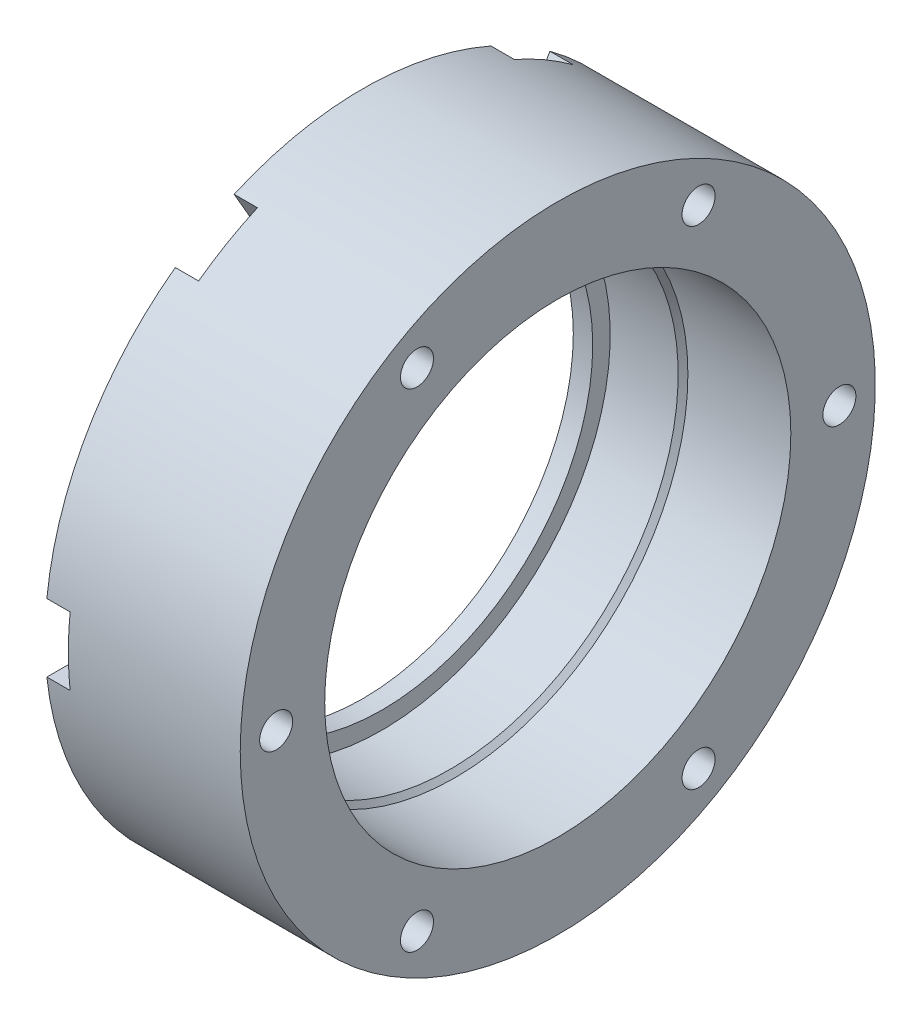
SolidWorks part; units mm, degrees
material "6063-T5"
ref_plane "Front" through (0, 0, 0) normal (0, 0, 1) x (1, 0, 0)
ref_plane "Top" through (0, 0, 0) normal (0, 1, 0) x (1, 0, 0)
ref_plane "Right" through (0, 0, 0) normal (1, 0, 0) x (0, 0, -1)
sketch "Croquis2" plane through (0, 0, 0) normal (0, 1, 0) x (1, 0, 0)
  line L0 (0, 32.7) -> (20.1, 32.7)
  line L1 (0, -55) -> (0, 55) construction
  line L2 (20.1, 32.7) -> (20.1, 24)
  line L3 (20.1, 24) -> (9.5, 24)
  line L4 (9.5, 24) -> (9, 23.5)
  line L5 (9, 23.5) -> (2, 23.5)
  line L6 (2, 23.5) -> (2, 21.7)
  line L7 (2, 21.7) -> (0, 21.7)
  line L8 (0, 21.7) -> (0, 32.7)
  line L9 (-55, 0) -> (55, 0) construction
  line L10 (-10.7507, 0) -> (41.8865, 0) construction
  dimension "D1" = 2
  dimension "D2" = 32.7
  dimension "D3" = 24
  dimension "D4" = 23.5
  dimension "D5" = 21.7
  dimension "D6" = 45
  dimension "D7" = 10.6
  dimension "D8" = 7
revolve "Revolución1" add sketch "Croquis2" angle 360 about L10
hole_wizard "Refrentado para tornillo con cabeza troncocónica de M31" positions "Croquis3" profile "Croquis5" counterbore size "M3" standard "Ansi Metric" end condition up to next
sketch "Croquis3" plane through (0, 0, 0) normal (-1, 0, 0) x (0, 0, 1)
  line L0 (0, 0) -> (14.5, 25.1147) construction
  line L3 (0, -11.055) -> (0, 11.055) construction
  point P0 (14.5, 25.1147)
  point P16 (29, 0)
  point P17 (14.5, -25.1147)
  point P18 (-14.5, -25.1147)
  point P19 (-29, 0)
  point P20 (-14.5, 25.1147)
  dimension "D1" = 29
  dimension "D2" = 30
  dimension "D3" = 6
sketch "Croquis5" plane through (0, 25.1147, 14.5) normal (0, 1, 0) x (0, 0, 1)
  line L0 (0, 0) -> (0, 20.1)
  line L1 (0, 20.1) -> (1.7, 20.1)
  line L3 (1.7, 20.1) -> (1.7, 2.4)
  line L4 (1.7, 2.4) -> (3.5, 2.4)
  line L5 (3.5, 2.4) -> (3.5, 0)
  line L7 (3.5, 0) -> (0, 0)
  line L11 (0, -6.35) -> (0, 107.95) construction
  dimension "Diámetro de taladro hasta el siguiente" = 3.4
  dimension "Profundidad de taladro hasta el siguiente" = 20.1
  dimension "Diámetro de refrentado" = 7
  dimension "Profundidad de refrentado" = 2.4
sketch "Croquis6" plane through (0, 0, 0) normal (-1, 0, 0) x (0, 0, 1)
  line L0 (29, 3.5) -> (32.5122, 3.5)
  line L1 (29, -3.5) -> (32.5122, -3.5)
  line L2 (17.5311, -23.3647) -> (19.2872, -26.4063)
  line L3 (11.4689, -26.8647) -> (13.225, -29.9063)
  line L4 (-11.4689, -26.8647) -> (-13.225, -29.9063)
  line L5 (-17.5311, -23.3647) -> (-19.2872, -26.4063)
  line L6 (-29, -3.5) -> (-32.5122, -3.5)
  line L7 (-29, 3.5) -> (-32.5122, 3.5)
  line L8 (-17.5311, 23.3647) -> (-19.2872, 26.4063)
  line L9 (-11.4689, 26.8647) -> (-13.225, 29.9063)
  line L10 (11.4689, 26.8647) -> (13.225, 29.9063)
  line L11 (17.5311, 23.3647) -> (19.2872, 26.4063)
  circle A0 centre (29, 0) radius 3.5 construction
  arc A1 (29, 3.5) -> (29, -3.5) centre (29, 0) ccw
  circle A2 centre (0, 0) radius 32.7 construction
  arc A3 (32.5122, -3.5) -> (32.5122, 3.5) centre (0, 0) ccw
  arc A4 (17.5311, -23.3647) -> (11.4689, -26.8647) centre (14.5, -25.1147) ccw
  arc A5 (13.225, -29.9063) -> (19.2872, -26.4063) centre (0, 0) ccw
  arc A6 (-11.4689, -26.8647) -> (-17.5311, -23.3647) centre (-14.5, -25.1147) ccw
  arc A7 (-19.2872, -26.4063) -> (-13.225, -29.9063) centre (0, 0) ccw
  arc A8 (-29, -3.5) -> (-29, 3.5) centre (-29, 0) ccw
  arc A9 (-32.5122, 3.5) -> (-32.5122, -3.5) centre (0, 0) ccw
  arc A10 (-17.5311, 23.3647) -> (-11.4689, 26.8647) centre (-14.5, 25.1147) ccw
  arc A11 (-13.225, 29.9063) -> (-19.2872, 26.4063) centre (0, 0) ccw
  arc A12 (11.4689, 26.8647) -> (17.5311, 23.3647) centre (14.5, 25.1147) ccw
  arc A13 (19.2872, 26.4063) -> (13.225, 29.9063) centre (0, 0) ccw
  dimension "D1" = 6
extrude "Cortar-Extruir1" cut sketch "Croquis6" against normal up to surface (2.4 mm away) up to face at (2.4, 25.1147, 16.2)
